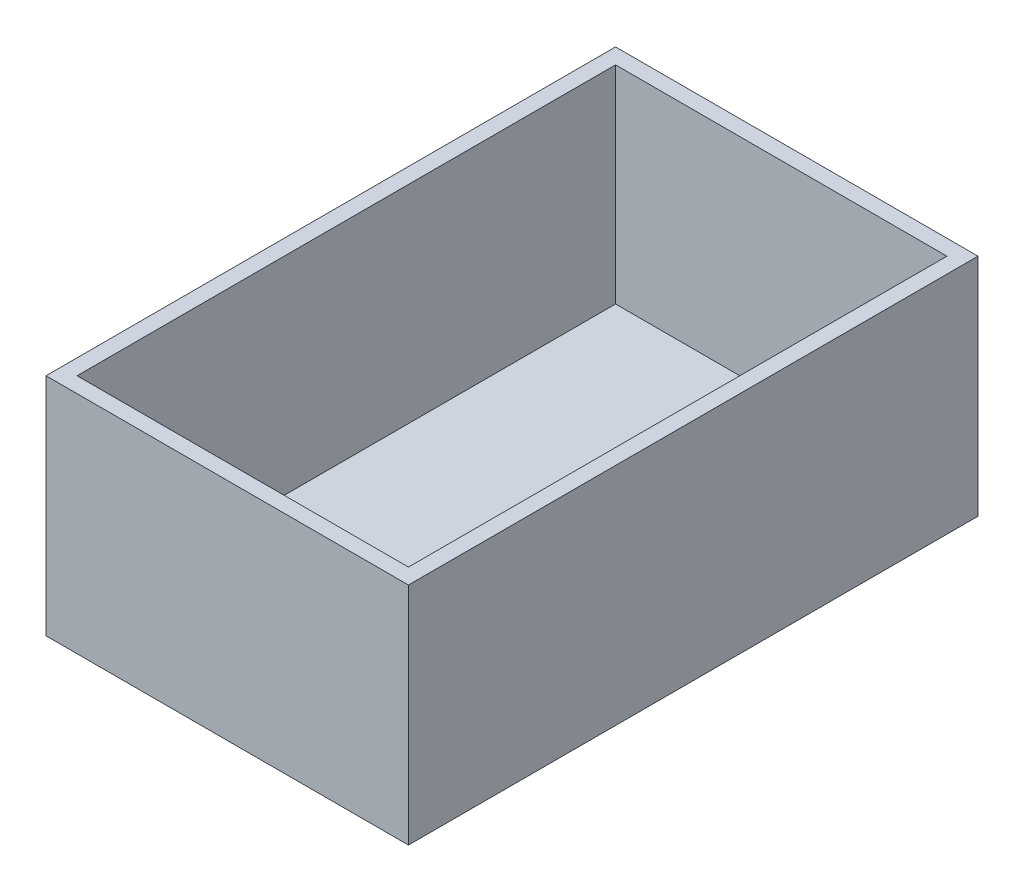
SolidWorks part; units mm, degrees
ref_plane "Front Plane" through (0, 0, 0) normal (0, 0, 1) x (1, 0, 0)
ref_plane "Top Plane" through (0, 0, 0) normal (0, 1, 0) x (1, 0, 0)
ref_plane "Right Plane" through (0, 0, 0) normal (1, 0, 0) x (0, 0, -1)
sketch "Base plate" plane through (0, 0, 0) normal (0, 1, 0) x (1, 0, 0)
  line L1 (35, -55) -> (-35, -55)
  line L2 (35, -55) -> (35, 55)
  line L3 (35, 55) -> (-35, 55)
  line L4 (-35, -55) -> (-35, 55)
  line L5 (35, -55) -> (-35, 55) construction
  line L6 (35, 55) -> (-35, -55) construction
  point P0 (0, 0)
  dimension "D1" = 110
  dimension "D2" = 70
extrude "Base plate EXT" add sketch "Base plate" along normal blind 3.5
sketch "Wall" plane through (0, 3.5, 0) normal (0, 1, 0) x (1, 0, 0)
  line L0 (-35, 55) -> (35, 55)
  line L1 (35, 55) -> (35, -55)
  line L2 (35, -55) -> (-35, -55)
  line L3 (-35, -55) -> (-35, 55)
  line L4 (-32, 52) -> (32, 52)
  line L5 (32, 52) -> (32, -52)
  line L6 (32, -52) -> (-32, -52)
  line L7 (-32, -52) -> (-32, 52)
  dimension "D1" = 3
  dimension "D2" = 3
  dimension "D3" = 3
  dimension "D4" = 3
extrude "Wall Ext" add sketch "Wall" along normal blind 40
equation "\"BOXWALL\"=3"
equation "\"D1@Wall\"=\"BOXWALL\""
equation "\"D2@Wall\"=\"BOXWALL\""
